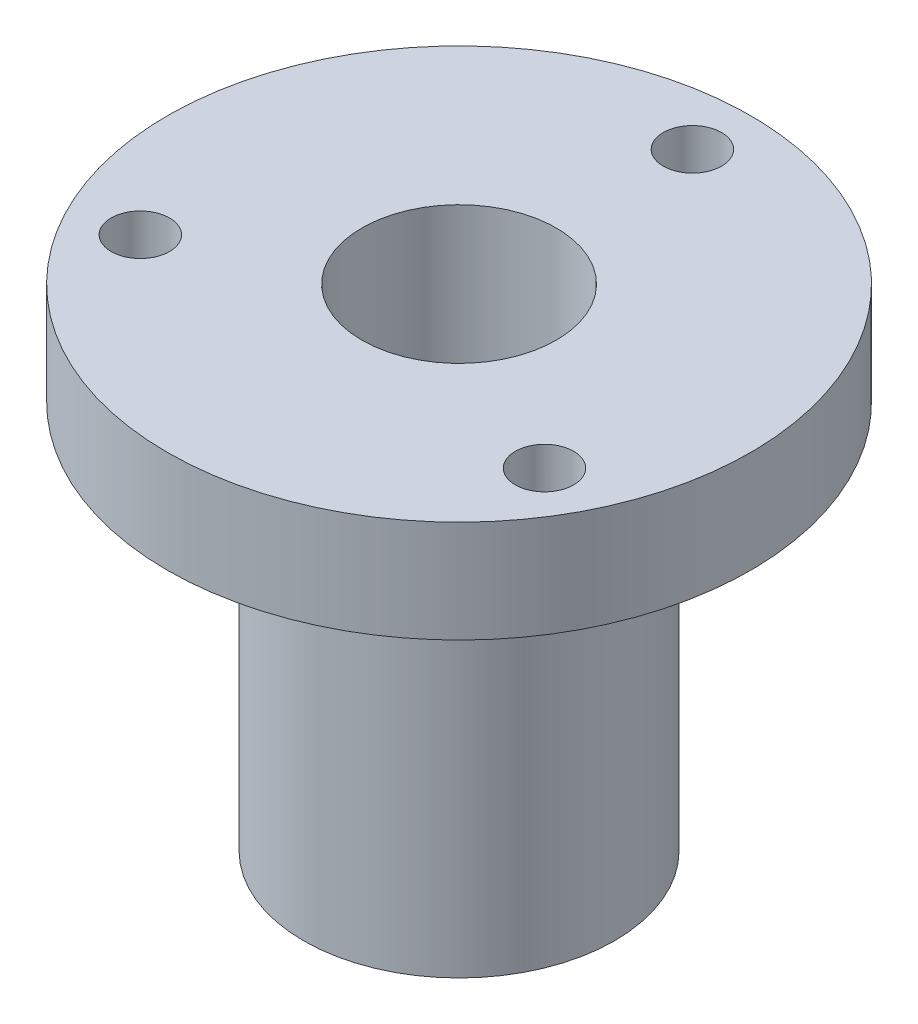
SolidWorks part; units mm, degrees
ref_plane "Front Plane" through (0, 0, 0) normal (0, 0, 1) x (1, 0, 0)
ref_plane "Top Plane" through (0, 0, 0) normal (0, 1, 0) x (1, 0, 0)
ref_plane "Right Plane" through (0, 0, 0) normal (1, 0, 0) x (0, 0, -1)
sketch "Sketch1" plane through (0, 0, 0) normal (0, 0, 1) x (1, 0, 0)
  line L0 (0, 6) -> (0, -6.5) construction
  line L1 (-5, 6.8269) -> (-5, -18.4231)
  line L2 (-5, -18.4231) -> (-8, -18.4231)
  line L3 (-8, -18.4231) -> (-8, 1.5769)
  line L4 (-8, 1.5769) -> (-15, 1.5769)
  line L5 (-15, 1.5769) -> (-15, 6.8269)
  line L6 (-15, 6.8269) -> (-5, 6.8269)
  dimension "D1" = 5
  dimension "D2" = 8
  dimension "D3" = 15
  dimension "D4" = 5.25
  dimension "D5" = 20
revolve "Revolve1" add sketch "Sketch1" angle 360 about L0
sketch "Sketch2" plane through (0, 6.8269, 0) normal (0, 1, 0) x (1, 0, 0)
  circle A0 centre (0, 12) radius 1.5
  dimension "D1" = 3
  dimension "D2" = 12
extrude "Cut-Extrude1" cut sketch "Sketch2" against normal blind 10
pattern_circular "CirPattern1" count 3 over 360 about axis through (0, 0, 0) along (0, 1, 0) of "Cut-Extrude1"
